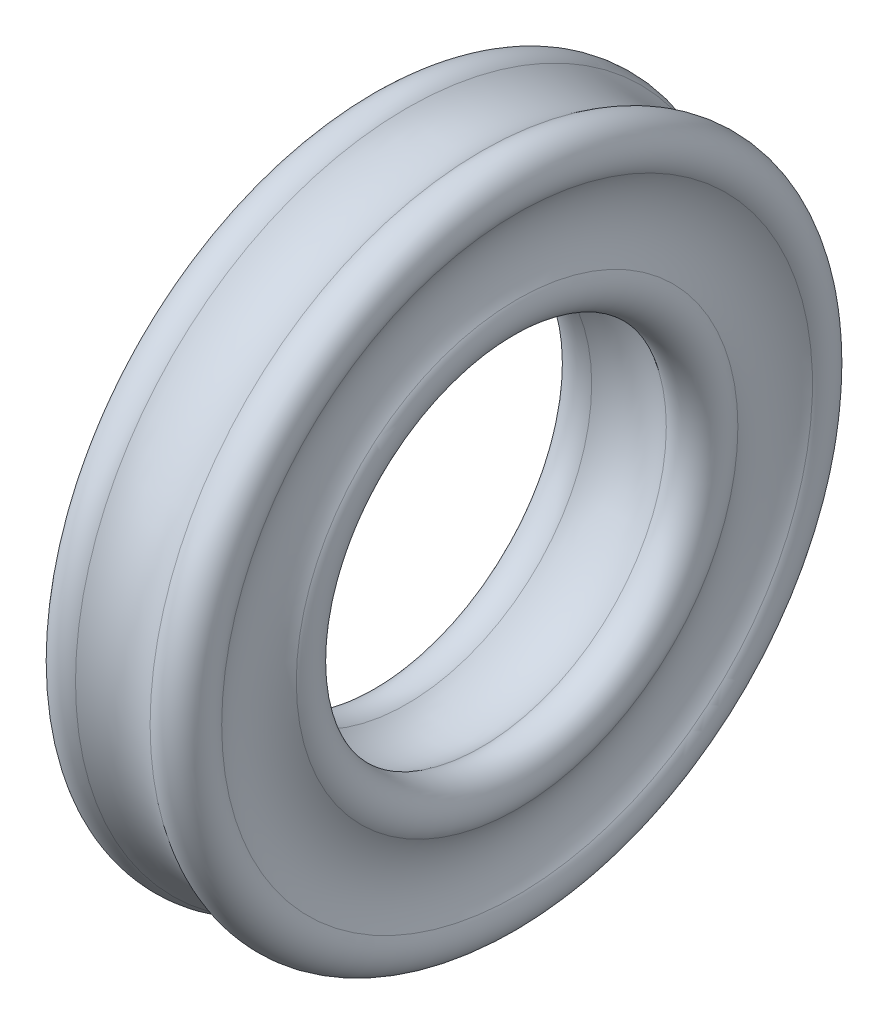
SolidWorks part; units mm, degrees
ref_plane "前基準面" through (0, 0, 0) normal (0, 0, 1) x (1, 0, 0)
ref_plane "上基準面" through (0, 0, 0) normal (0, 1, 0) x (1, 0, 0)
ref_plane "右基準面" through (0, 0, 0) normal (1, 0, 0) x (0, 0, -1)
sketch "草圖1" plane through (0, 0, 0) normal (0, 0, 1) x (1, 0, 0)
  line L0 (0, 0) -> (50.6225, 0) construction
  line L2 (0, 200) -> (83.0582, 200) construction
  line L3 (0, 326.361) -> (0, 0) construction
  arc A0 (56.641, 228.906) -> (56.641, 171.094) centre (100, 200) ccw
  arc A1 (-28.906, 256.641) -> (28.906, 256.641) centre (0, 300) ccw
  arc A2 (28.906, 256.641) -> (56.641, 228.906) centre (40, 240) cw
  arc A3 (28.906, 143.359) -> (56.641, 171.094) centre (40, 160) ccw
  arc A4 (-28.906, 256.641) -> (-56.641, 228.906) centre (-40, 240) ccw
  arc A5 (-28.906, 143.359) -> (-56.641, 171.094) centre (-40, 160) cw
  arc A6 (-56.641, 228.906) -> (-56.641, 171.094) centre (-100, 200) cw
  arc A7 (-28.906, 143.359) -> (28.906, 143.359) centre (0, 100) cw
  dimension "D1" = 20
  dimension "D3" = 40
  dimension "D6" = 100
  dimension "D2" = 200
  dimension "D4" = 40
  dimension "D5" = 100
revolve "旋轉1" add sketch "草圖1" angle 360 about L0
